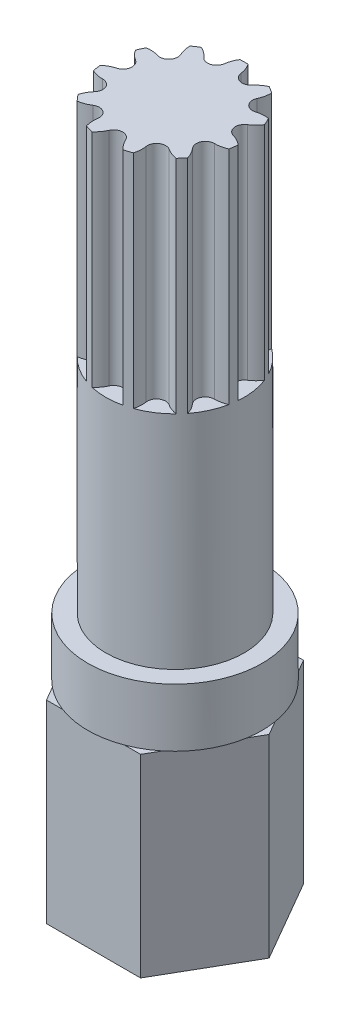
SolidWorks part; units mm, degrees
ref_plane "Front Plane" through (0, 0, 0) normal (0, 0, 1) x (1, 0, 0)
ref_plane "Top Plane" through (0, 0, 0) normal (0, 1, 0) x (1, 0, 0)
ref_plane "Right Plane" through (0, 0, 0) normal (1, 0, 0) x (0, 0, -1)
sketch "Sketch1" plane through (0, 0, 0) normal (0, 1, 0) x (1, 0, 0)
  circle A0 centre (0, 0) radius 3.15
  dimension "D1" = 6.3
extrude "Boss-Extrude1" add sketch "Sketch1" along normal blind 2.1
sketch "Sketch2" plane through (0, 2.1, 0) normal (0, 1, 0) x (1, 0, 0)
  circle A0 centre (0, 0) radius 2.5
  dimension "D1" = 5
extrude "Boss-Extrude3" add sketch "Sketch2" along normal blind 16
sketch "Gear Profile" plane through (0, 0, 0) normal (0, -1, 0) x (1, 0, 0)
  line L420 (-1.6777, -5.4575) -> (-1.7402, -5.3144)
  line L421 (-1.7402, -5.3144) -> (-1.7939, -5.1757)
  line L422 (-1.7939, -5.1757) -> (-1.8392, -5.0423)
  line L423 (-1.8392, -5.0423) -> (-1.8764, -4.916)
  line L424 (-1.8764, -4.916) -> (-1.9071, -4.7932)
  line L425 (-1.9071, -4.7932) -> (-1.9311, -4.676)
  line L426 (-1.9311, -4.676) -> (-1.9488, -4.5668)
  line L427 (-1.9488, -4.5668) -> (-1.961, -4.464)
  line L428 (-1.961, -4.464) -> (-1.9715, -4.2798)
  line L429 (-1.9715, -4.2798) -> (-1.9674, -4.1246)
  line L430 (-1.9674, -4.1246) -> (-1.9537, -4.0009)
  line L431 (-1.9537, -4.0009) -> (-1.9303, -3.8867)
  line L432 (-1.9303, -3.8867) -> (-1.8594, -3.8097)
  line L433 (-1.8594, -3.8097) -> (-1.7784, -3.7125)
  line L434 (-1.7784, -3.7125) -> (-1.7087, -3.6155)
  line L435 (-1.7087, -3.6155) -> (-1.6501, -3.5195)
  line L436 (-1.6501, -3.5195) -> (-1.6023, -3.4251)
  line L437 (-1.6023, -3.4251) -> (-1.5652, -3.3333)
  line L438 (-1.5652, -3.3333) -> (-1.5384, -3.2446)
  line L439 (-1.5384, -3.2446) -> (-1.5215, -3.1597)
  line L440 (-1.5215, -3.1597) -> (-1.5143, -3.0795)
  line L441 (-1.5143, -3.0795) -> (-1.5162, -3.0043)
  line L442 (-1.5162, -3.0043) -> (-1.5269, -2.935)
  line L443 (-1.5269, -2.935) -> (-1.5457, -2.8721)
  line L444 (-1.5457, -2.8721) -> (-1.5723, -2.8162)
  line L445 (-1.5723, -2.8162) -> (-1.606, -2.7677)
  line L446 (-1.606, -2.7677) -> (-1.6572, -2.7183)
  line L447 (-1.6572, -2.7183) -> (-1.8447, -2.5928)
  line L448 (-1.8447, -2.5928) -> (-1.984, -2.4878)
  line L449 (-1.984, -2.4878) -> (-2.1173, -2.3754)
  line L450 (-2.1173, -2.3754) -> (-2.2814, -2.2205)
  line L451 (-2.2814, -2.2205) -> (-2.341, -2.1815)
  line L452 (-2.341, -2.1815) -> (-2.3957, -2.1595)
  line L453 (-2.3957, -2.1595) -> (-2.4562, -2.146)
  line L454 (-2.4562, -2.146) -> (-2.5217, -2.1417)
  line L455 (-2.5217, -2.1417) -> (-2.5917, -2.1467)
  line L456 (-2.5917, -2.1467) -> (-2.6653, -2.1615)
  line L457 (-2.6653, -2.1615) -> (-2.742, -2.1865)
  line L458 (-2.742, -2.1865) -> (-2.8209, -2.2218)
  line L459 (-2.8209, -2.2218) -> (-2.9014, -2.2676)
  line L460 (-2.9014, -2.2676) -> (-2.9827, -2.3243)
  line L461 (-2.9827, -2.3243) -> (-3.0641, -2.3918)
  line L462 (-3.0641, -2.3918) -> (-3.1447, -2.4703)
  line L463 (-3.1447, -2.4703) -> (-3.2237, -2.5599)
  line L464 (-3.2237, -2.5599) -> (-3.3005, -2.6605)
  line L465 (-3.3005, -2.6605) -> (-3.3598, -2.7467)
  line L466 (-3.3598, -2.7467) -> (-3.4659, -2.795)
  line L467 (-3.4659, -2.795) -> (-3.5835, -2.8358)
  line L468 (-3.5835, -2.8358) -> (-3.7338, -2.8744)
  line L469 (-3.7338, -2.8744) -> (-3.9158, -2.9052)
  line L470 (-3.9158, -2.9052) -> (-4.0187, -2.9161)
  line L471 (-4.0187, -2.9161) -> (-4.1291, -2.9232)
  line L472 (-4.1291, -2.9232) -> (-4.2487, -2.9258)
  line L473 (-4.2487, -2.9258) -> (-4.3752, -2.9233)
  line L474 (-4.3752, -2.9233) -> (-4.5067, -2.9151)
  line L475 (-4.5067, -2.9151) -> (-4.6468, -2.9006)
  line L476 (-4.6468, -2.9006) -> (-4.794, -2.8791)
  line L477 (-4.794, -2.8791) -> (-4.9474, -2.85)
  line L478 (-4.9474, -2.85) -> (-5.0902, -2.8167)
  line L479 (-5.3759, -2.2235) -> (-5.3129, -2.0911)
  line L480 (-5.3129, -2.0911) -> (-5.2399, -1.953)
  line L481 (-5.2399, -1.953) -> (-5.165, -1.8245)
  line L482 (-5.165, -1.8245) -> (-5.089, -1.7059)
  line L483 (-5.089, -1.7059) -> (-5.0134, -1.5981)
  line L484 (-5.0134, -1.5981) -> (-4.9365, -1.4976)
  line L485 (-4.9365, -1.4976) -> (-4.8599, -1.4057)
  line L486 (-4.8599, -1.4057) -> (-4.7855, -1.3238)
  line L487 (-4.7855, -1.3238) -> (-4.7128, -1.2502)
  line L488 (-4.7128, -1.2502) -> (-4.5753, -1.1271)
  line L489 (-4.5753, -1.1271) -> (-4.4514, -1.0336)
  line L490 (-4.4514, -1.0336) -> (-4.3462, -0.9671)
  line L491 (-4.3462, -0.9671) -> (-4.2422, -0.9142)
  line L492 (-4.2422, -0.9142) -> (-4.1379, -0.9217)
  line L493 (-4.1379, -0.9217) -> (-4.0114, -0.9244)
  line L494 (-4.0114, -0.9244) -> (-3.8921, -0.9184)
  line L495 (-3.8921, -0.9184) -> (-3.7804, -0.9043)
  line L496 (-3.7804, -0.9043) -> (-3.6769, -0.8828)
  line L497 (-3.6769, -0.8828) -> (-3.5819, -0.8546)
  line L498 (-3.5819, -0.8546) -> (-3.4959, -0.8203)
  line L499 (-3.4959, -0.8203) -> (-3.4191, -0.7805)
  line L500 (-3.4191, -0.7805) -> (-3.3518, -0.7361)
  line L501 (-3.3518, -0.7361) -> (-3.2942, -0.6878)
  line L502 (-3.2942, -0.6878) -> (-3.2467, -0.6363)
  line L503 (-3.2467, -0.6363) -> (-3.2093, -0.5823)
  line L504 (-3.2093, -0.5823) -> (-3.1821, -0.5267)
  line L505 (-3.1821, -0.5267) -> (-3.1652, -0.4701)
  line L506 (-3.1652, -0.4701) -> (-3.1585, -0.3992)
  line L507 (-3.1585, -0.3992) -> (-3.1773, -0.1744)
  line L508 (-3.1773, -0.1744) -> (-3.1821, 0)
  line L509 (-3.1821, 0) -> (-3.1773, 0.1743)
  line L510 (-3.1773, 0.1743) -> (-3.1585, 0.3991)
  line L511 (-3.1585, 0.3991) -> (-3.1652, 0.47)
  line L512 (-3.1652, 0.47) -> (-3.1821, 0.5266)
  line L513 (-3.1821, 0.5266) -> (-3.2093, 0.5822)
  line L514 (-3.2093, 0.5822) -> (-3.2467, 0.6362)
  line L515 (-3.2467, 0.6362) -> (-3.2942, 0.6877)
  line L516 (-3.2942, 0.6877) -> (-3.3518, 0.7361)
  line L517 (-3.3518, 0.7361) -> (-3.4191, 0.7805)
  line L518 (-3.4191, 0.7805) -> (-3.4959, 0.8202)
  line L519 (-3.4959, 0.8202) -> (-3.5819, 0.8545)
  line L520 (-3.5819, 0.8545) -> (-3.6769, 0.8828)
  line L521 (-3.6769, 0.8828) -> (-3.7804, 0.9043)
  line L522 (-3.7804, 0.9043) -> (-3.8921, 0.9183)
  line L523 (-3.8921, 0.9183) -> (-4.0114, 0.9243)
  line L524 (-4.0114, 0.9243) -> (-4.1379, 0.9216)
  line L525 (-4.1379, 0.9216) -> (-4.2422, 0.9142)
  line L526 (-4.2422, 0.9142) -> (-4.3462, 0.967)
  line L527 (-4.3462, 0.967) -> (-4.4514, 1.0335)
  line L528 (-4.4514, 1.0335) -> (-4.5753, 1.127)
  line L529 (-4.5753, 1.127) -> (-4.7128, 1.2501)
  line L530 (-4.7128, 1.2501) -> (-4.7855, 1.3238)
  line L531 (-4.7855, 1.3238) -> (-4.8599, 1.4056)
  line L532 (-4.8599, 1.4056) -> (-4.9365, 1.4975)
  line L533 (-4.9365, 1.4975) -> (-5.0134, 1.598)
  line L534 (-5.0134, 1.598) -> (-5.089, 1.7059)
  line L535 (-5.089, 1.7059) -> (-5.165, 1.8244)
  line L536 (-5.165, 1.8244) -> (-5.2399, 1.9529)
  line L537 (-5.2399, 1.9529) -> (-5.3129, 2.0911)
  line L538 (-5.3129, 2.0911) -> (-5.3759, 2.2234)
  line L539 (-5.0902, 2.8167) -> (-4.9474, 2.8499)
  line L540 (-4.9474, 2.8499) -> (-4.794, 2.879)
  line L541 (-4.794, 2.879) -> (-4.6468, 2.9005)
  line L542 (-4.6468, 2.9005) -> (-4.5067, 2.9151)
  line L543 (-4.5067, 2.9151) -> (-4.3752, 2.9232)
  line L544 (-4.3752, 2.9232) -> (-4.2487, 2.9257)
  line L545 (-4.2487, 2.9257) -> (-4.1291, 2.9231)
  line L546 (-4.1291, 2.9231) -> (-4.0187, 2.916)
  line L547 (-4.0187, 2.916) -> (-3.9158, 2.9051)
  line L548 (-3.9158, 2.9051) -> (-3.7338, 2.8743)
  line L549 (-3.7338, 2.8743) -> (-3.5835, 2.8358)
  line L550 (-3.5835, 2.8358) -> (-3.4659, 2.7949)
  line L551 (-3.4659, 2.7949) -> (-3.3598, 2.7466)
  line L552 (-3.3598, 2.7466) -> (-3.3005, 2.6604)
  line L553 (-3.3005, 2.6604) -> (-3.2237, 2.5598)
  line L554 (-3.2237, 2.5598) -> (-3.1447, 2.4703)
  line L555 (-3.1447, 2.4703) -> (-3.0641, 2.3918)
  line L556 (-3.0641, 2.3918) -> (-2.9827, 2.3242)
  line L557 (-2.9827, 2.3242) -> (-2.9014, 2.2676)
  line L558 (-2.9014, 2.2676) -> (-2.8209, 2.2217)
  line L559 (-2.8209, 2.2217) -> (-2.742, 2.1864)
  line L560 (-2.742, 2.1864) -> (-2.6653, 2.1615)
  line L561 (-2.6653, 2.1615) -> (-2.5917, 2.1466)
  line L562 (-2.5917, 2.1466) -> (-2.5217, 2.1416)
  line L563 (-2.5217, 2.1416) -> (-2.4562, 2.146)
  line L564 (-2.4562, 2.146) -> (-2.3957, 2.1594)
  line L565 (-2.3957, 2.1594) -> (-2.341, 2.1815)
  line L566 (-2.341, 2.1815) -> (-2.2814, 2.2205)
  line L567 (-2.2814, 2.2205) -> (-2.1173, 2.3753)
  line L568 (-2.1173, 2.3753) -> (-1.984, 2.4878)
  line L569 (-1.984, 2.4878) -> (-1.8447, 2.5927)
  line L570 (-1.8447, 2.5927) -> (-1.6572, 2.7182)
  line L571 (-1.6572, 2.7182) -> (-1.606, 2.7676)
  line L572 (-1.606, 2.7676) -> (-1.5723, 2.8161)
  line L573 (-1.5723, 2.8161) -> (-1.5457, 2.8721)
  line L574 (-1.5457, 2.8721) -> (-1.5269, 2.935)
  line L575 (-1.5269, 2.935) -> (-1.5162, 3.0043)
  line L576 (-1.5162, 3.0043) -> (-1.5143, 3.0794)
  line L577 (-1.5143, 3.0794) -> (-1.5215, 3.1597)
  line L578 (-1.5215, 3.1597) -> (-1.5384, 3.2445)
  line L579 (-1.5384, 3.2445) -> (-1.5652, 3.3332)
  line L580 (-1.5652, 3.3332) -> (-1.6023, 3.4251)
  line L581 (-1.6023, 3.4251) -> (-1.6501, 3.5194)
  line L582 (-1.6501, 3.5194) -> (-1.7087, 3.6154)
  line L583 (-1.7087, 3.6154) -> (-1.7784, 3.7125)
  line L584 (-1.7784, 3.7125) -> (-1.8594, 3.8097)
  line L585 (-1.8594, 3.8097) -> (-1.9303, 3.8866)
  line L586 (-1.9303, 3.8866) -> (-1.9537, 4.0009)
  line L587 (-1.9537, 4.0009) -> (-1.9674, 4.1246)
  line L588 (-1.9674, 4.1246) -> (-1.9715, 4.2797)
  line L589 (-1.9715, 4.2797) -> (-1.961, 4.464)
  line L590 (-1.961, 4.464) -> (-1.9488, 4.5668)
  line L591 (-1.9488, 4.5668) -> (-1.9311, 4.6759)
  line L592 (-1.9311, 4.6759) -> (-1.9071, 4.7932)
  line L593 (-1.9071, 4.7932) -> (-1.8764, 4.9159)
  line L594 (-1.8764, 4.9159) -> (-1.8392, 5.0423)
  line L595 (-1.8392, 5.0423) -> (-1.7939, 5.1756)
  line L596 (-1.7939, 5.1756) -> (-1.7402, 5.3143)
  line L597 (-1.7402, 5.3143) -> (-1.6777, 5.4575)
  line L598 (-1.6777, 5.4575) -> (-1.6135, 5.5893)
  line L599 (-0.9715, 5.7358) -> (-0.8565, 5.6449)
  line L600 (-0.8565, 5.6449) -> (-0.7381, 5.543)
  line L601 (-0.7381, 5.543) -> (-0.6295, 5.4414)
  line L602 (-0.6295, 5.4414) -> (-0.5308, 5.3409)
  line L603 (-0.5308, 5.3409) -> (-0.4425, 5.2432)
  line L604 (-0.4425, 5.2432) -> (-0.3616, 5.1459)
  line L605 (-0.3616, 5.1459) -> (-0.2891, 5.0507)
  line L606 (-0.2891, 5.0507) -> (-0.2258, 4.96)
  line L607 (-0.2258, 4.96) -> (-0.1702, 4.8727)
  line L608 (-0.1702, 4.8727) -> (-0.0808, 4.7113)
  line L609 (-0.0808, 4.7113) -> (-0.0172, 4.5697)
  line L610 (-0.0172, 4.5697) -> (0.0242, 4.4523)
  line L611 (0.0242, 4.4523) -> (0.0526, 4.3392)
  line L612 (0.0526, 4.3392) -> (0.0222, 4.2391)
  line L613 (0.0222, 4.2391) -> (-0.0086, 4.1164)
  line L614 (-0.0086, 4.1164) -> (-0.0293, 3.9987)
  line L615 (-0.0293, 3.9987) -> (-0.0405, 3.8868)
  line L616 (-0.0405, 3.8868) -> (-0.0426, 3.7811)
  line L617 (-0.0426, 3.7811) -> (-0.0362, 3.6822)
  line L618 (-0.0362, 3.6822) -> (-0.0218, 3.5907)
  line L619 (-0.0218, 3.5907) -> (-0.0002, 3.5069)
  line L620 (-0.0002, 3.5069) -> (0.0281, 3.4314)
  line L621 (0.0281, 3.4314) -> (0.0624, 3.3646)
  line L622 (0.0624, 3.3646) -> (0.1021, 3.3068)
  line L623 (0.1021, 3.3068) -> (0.1464, 3.2583)
  line L624 (0.1464, 3.2583) -> (0.1946, 3.2194)
  line L625 (0.1946, 3.2194) -> (0.246, 3.1903)
  line L626 (0.246, 3.1903) -> (0.3136, 3.1681)
  line L627 (0.3136, 3.1681) -> (0.537, 3.1363)
  line L628 (0.537, 3.1363) -> (0.708, 3.1022)
  line L629 (0.708, 3.1022) -> (0.8769, 3.0588)
  line L630 (0.8769, 3.0588) -> (1.0919, 2.9904)
  line L631 (1.0919, 2.9904) -> (1.1625, 2.9811)
  line L632 (1.1625, 2.9811) -> (1.2214, 2.985)
  line L633 (1.2214, 2.985) -> (1.2817, 2.9991)
  line L634 (1.2817, 2.9991) -> (1.3427, 3.0236)
  line L635 (1.3427, 3.0236) -> (1.4035, 3.0585)
  line L636 (1.4035, 3.0585) -> (1.4634, 3.1038)
  line L637 (1.4634, 3.1038) -> (1.5217, 3.1596)
  line L638 (1.5217, 3.1596) -> (1.5775, 3.2256)
  line L639 (1.5775, 3.2256) -> (1.6301, 3.3019)
  line L640 (1.6301, 3.3019) -> (1.6788, 3.3882)
  line L641 (1.6788, 3.3882) -> (1.7228, 3.4843)
  line L642 (1.7228, 3.4843) -> (1.7613, 3.59)
  line L643 (1.7613, 3.59) -> (1.7937, 3.705)
  line L644 (1.7937, 3.705) -> (1.8192, 3.829)
  line L645 (1.8192, 3.829) -> (1.8352, 3.9324)
  line L646 (1.8352, 3.9324) -> (1.9099, 4.0219)
  line L647 (1.9099, 4.0219) -> (1.9981, 4.1097)
  line L648 (1.9981, 4.1097) -> (2.1168, 4.2097)
  line L649 (2.1168, 4.2097) -> (2.2674, 4.3164)
  line L650 (2.2674, 4.3164) -> (2.3554, 4.3709)
  line L651 (2.3554, 4.3709) -> (2.4518, 4.4251)
  line L652 (2.4518, 4.4251) -> (2.5584, 4.4794)
  line L653 (2.5584, 4.4794) -> (2.6735, 4.532)
  line L654 (2.6735, 4.532) -> (2.7955, 4.5817)
  line L655 (2.7955, 4.5817) -> (2.928, 4.6294)
  line L656 (2.928, 4.6294) -> (3.0699, 4.6739)
  line L657 (3.0699, 4.6739) -> (3.2208, 4.7143)
  line L658 (3.2208, 4.7143) -> (3.3639, 4.7463)
  line L659 (3.8787, 4.3357) -> (3.8793, 4.1891)
  line L660 (3.8793, 4.1891) -> (3.8735, 4.033)
  line L661 (3.8735, 4.033) -> (3.8618, 3.8847)
  line L662 (3.8618, 3.8847) -> (3.8448, 3.7449)
  line L663 (3.8448, 3.7449) -> (3.8234, 3.615)
  line L664 (3.8234, 3.615) -> (3.7978, 3.4911)
  line L665 (3.7978, 3.4911) -> (3.7686, 3.375)
  line L666 (3.7686, 3.375) -> (3.7371, 3.269)
  line L667 (3.7371, 3.269) -> (3.7036, 3.1711)
  line L668 (3.7036, 3.1711) -> (3.6331, 3.0005)
  line L669 (3.6331, 3.0005) -> (3.562, 2.8625)
  line L670 (3.562, 2.8625) -> (3.4961, 2.757)
  line L671 (3.4961, 2.757) -> (3.4253, 2.6643)
  line L672 (3.4253, 2.6643) -> (3.3281, 2.6257)
  line L673 (3.3281, 2.6257) -> (3.213, 2.5732)
  line L674 (3.213, 2.5732) -> (3.1081, 2.516)
  line L675 (3.1081, 2.516) -> (3.0136, 2.4549)
  line L676 (3.0136, 2.4549) -> (2.9296, 2.3907)
  line L677 (2.9296, 2.3907) -> (2.8563, 2.324)
  line L678 (2.8563, 2.324) -> (2.7937, 2.2557)
  line L679 (2.7937, 2.2557) -> (2.7417, 2.1866)
  line L680 (2.7417, 2.1866) -> (2.7003, 2.1174)
  line L681 (2.7003, 2.1174) -> (2.6695, 2.0489)
  line L682 (2.6695, 2.0489) -> (2.649, 1.9819)
  line L683 (2.649, 1.9819) -> (2.6387, 1.917)
  line L684 (2.6387, 1.917) -> (2.6383, 1.8551)
  line L685 (2.6383, 1.8551) -> (2.6476, 1.7967)
  line L686 (2.6476, 1.7967) -> (2.6724, 1.73)
  line L687 (2.6724, 1.73) -> (2.7869, 1.5356)
  line L688 (2.7869, 1.5356) -> (2.8668, 1.3806)
  line L689 (2.8668, 1.3806) -> (2.9382, 1.2215)
  line L690 (2.9382, 1.2215) -> (3.0188, 1.0107)
  line L691 (3.0188, 1.0107) -> (3.0555, 0.9498)
  line L692 (3.0555, 0.9498) -> (3.0953, 0.9061)
  line L693 (3.0953, 0.9061) -> (3.144, 0.8678)
  line L694 (3.144, 0.8678) -> (3.2011, 0.8354)
  line L695 (3.2011, 0.8354) -> (3.2663, 0.8096)
  line L696 (3.2663, 0.8096) -> (3.3391, 0.791)
  line L697 (3.3391, 0.791) -> (3.419, 0.7802)
  line L698 (3.419, 0.7802) -> (3.5054, 0.7777)
  line L699 (3.5054, 0.7777) -> (3.5979, 0.7842)
  line L700 (3.5979, 0.7842) -> (3.6957, 0.7999)
  line L701 (3.6957, 0.7999) -> (3.7983, 0.8255)
  line L702 (3.7983, 0.8255) -> (3.905, 0.8612)
  line L703 (3.905, 0.8612) -> (4.0151, 0.9076)
  line L704 (4.0151, 0.9076) -> (4.1279, 0.9649)
  line L705 (4.1279, 0.9649) -> (4.2187, 1.0169)
  line L706 (4.2187, 1.0169) -> (4.3353, 1.0144)
  line L707 (4.3353, 1.0144) -> (4.4589, 1.0001)
  line L708 (4.4589, 1.0001) -> (4.6111, 0.9696)
  line L709 (4.6111, 0.9696) -> (4.7884, 0.9184)
  line L710 (4.7884, 0.9184) -> (4.8859, 0.8836)
  line L711 (4.8859, 0.8836) -> (4.9884, 0.8421)
  line L712 (4.9884, 0.8421) -> (5.0973, 0.7926)
  line L713 (5.0973, 0.7926) -> (5.2102, 0.7354)
  line L714 (5.2102, 0.7354) -> (5.3251, 0.671)
  line L715 (5.3251, 0.671) -> (5.445, 0.5972)
  line L716 (5.445, 0.5972) -> (5.5683, 0.5139)
  line L717 (5.5683, 0.5139) -> (5.6939, 0.4211)
  line L718 (5.6939, 0.4211) -> (5.8081, 0.3292)
  line L719 (5.8081, -0.3293) -> (5.6939, -0.4212)
  line L720 (5.6939, -0.4212) -> (5.5683, -0.514)
  line L721 (5.5683, -0.514) -> (5.445, -0.5972)
  line L722 (5.445, -0.5972) -> (5.3251, -0.6711)
  line L723 (5.3251, -0.6711) -> (5.2102, -0.7354)
  line L724 (5.2102, -0.7354) -> (5.0973, -0.7926)
  line L725 (5.0973, -0.7926) -> (4.9884, -0.8421)
  line L726 (4.9884, -0.8421) -> (4.8859, -0.8837)
  line L727 (4.8859, -0.8837) -> (4.7884, -0.9185)
  line L728 (4.7884, -0.9185) -> (4.6111, -0.9697)
  line L729 (4.6111, -0.9697) -> (4.4589, -1.0002)
  line L730 (4.4589, -1.0002) -> (4.3353, -1.0144)
  line L731 (4.3353, -1.0144) -> (4.2187, -1.017)
  line L732 (4.2187, -1.017) -> (4.1279, -0.965)
  line L733 (4.1279, -0.965) -> (4.0151, -0.9077)
  line L734 (4.0151, -0.9077) -> (3.905, -0.8613)
  line L735 (3.905, -0.8613) -> (3.7983, -0.8255)
  line L736 (3.7983, -0.8255) -> (3.6957, -0.8)
  line L737 (3.6957, -0.8) -> (3.5979, -0.7842)
  line L738 (3.5979, -0.7842) -> (3.5054, -0.7778)
  line L739 (3.5054, -0.7778) -> (3.419, -0.7803)
  line L740 (3.419, -0.7803) -> (3.3391, -0.7911)
  line L741 (3.3391, -0.7911) -> (3.2663, -0.8097)
  line L742 (3.2663, -0.8097) -> (3.2011, -0.8354)
  line L743 (3.2011, -0.8354) -> (3.144, -0.8678)
  line L744 (3.144, -0.8678) -> (3.0953, -0.9062)
  line L745 (3.0953, -0.9062) -> (3.0555, -0.9498)
  line L746 (3.0555, -0.9498) -> (3.0188, -1.0108)
  line L747 (3.0188, -1.0108) -> (2.9382, -1.2215)
  line L748 (2.9382, -1.2215) -> (2.8668, -1.3806)
  line L749 (2.8668, -1.3806) -> (2.7869, -1.5356)
  line L750 (2.7869, -1.5356) -> (2.6724, -1.7301)
  line L751 (2.6724, -1.7301) -> (2.6476, -1.7968)
  line L752 (2.6476, -1.7968) -> (2.6383, -1.8551)
  line L753 (2.6383, -1.8551) -> (2.6387, -1.9171)
  line L754 (2.6387, -1.9171) -> (2.649, -1.9819)
  line L755 (2.649, -1.9819) -> (2.6695, -2.049)
  line L756 (2.6695, -2.049) -> (2.7003, -2.1175)
  line L757 (2.7003, -2.1175) -> (2.7417, -2.1867)
  line L758 (2.7417, -2.1867) -> (2.7937, -2.2558)
  line L759 (2.7937, -2.2558) -> (2.8563, -2.3241)
  line L760 (2.8563, -2.3241) -> (2.9296, -2.3907)
  line L761 (2.9296, -2.3907) -> (3.0136, -2.455)
  line L762 (3.0136, -2.455) -> (3.1081, -2.5161)
  line L763 (3.1081, -2.5161) -> (3.213, -2.5733)
  line L764 (3.213, -2.5733) -> (3.3281, -2.6257)
  line L765 (3.3281, -2.6257) -> (3.4253, -2.6643)
  line L766 (3.4253, -2.6643) -> (3.4961, -2.757)
  line L767 (3.4961, -2.757) -> (3.562, -2.8626)
  line L768 (3.562, -2.8626) -> (3.6331, -3.0006)
  line L769 (3.6331, -3.0006) -> (3.7036, -3.1711)
  line L770 (3.7036, -3.1711) -> (3.7371, -3.2691)
  line L771 (3.7371, -3.2691) -> (3.7686, -3.3751)
  line L772 (3.7686, -3.3751) -> (3.7978, -3.4911)
  line L773 (3.7978, -3.4911) -> (3.8234, -3.615)
  line L774 (3.8234, -3.615) -> (3.8448, -3.745)
  line L775 (3.8448, -3.745) -> (3.8618, -3.8848)
  line L776 (3.8618, -3.8848) -> (3.8735, -4.0331)
  line L777 (3.8735, -4.0331) -> (3.8793, -4.1892)
  line L778 (3.8793, -4.1892) -> (3.8787, -4.3358)
  line L779 (3.3639, -4.7463) -> (3.2208, -4.7143)
  line L780 (3.2208, -4.7143) -> (3.0699, -4.6739)
  line L781 (3.0699, -4.6739) -> (2.928, -4.6295)
  line L782 (2.928, -4.6295) -> (2.7955, -4.5818)
  line L783 (2.7955, -4.5818) -> (2.6735, -4.5321)
  line L784 (2.6735, -4.5321) -> (2.5584, -4.4795)
  line L785 (2.5584, -4.4795) -> (2.4518, -4.4252)
  line L786 (2.4518, -4.4252) -> (2.3554, -4.3709)
  line L787 (2.3554, -4.3709) -> (2.2674, -4.3164)
  line L788 (2.2674, -4.3164) -> (2.1168, -4.2097)
  line L789 (2.1168, -4.2097) -> (1.9981, -4.1098)
  line L790 (1.9981, -4.1098) -> (1.9099, -4.022)
  line L791 (1.9099, -4.022) -> (1.8352, -3.9324)
  line L792 (1.8352, -3.9324) -> (1.8192, -3.829)
  line L793 (1.8192, -3.829) -> (1.7937, -3.7051)
  line L794 (1.7937, -3.7051) -> (1.7613, -3.5901)
  line L795 (1.7613, -3.5901) -> (1.7228, -3.4844)
  line L796 (1.7228, -3.4844) -> (1.6788, -3.3883)
  line L797 (1.6788, -3.3883) -> (1.6301, -3.3019)
  line L798 (1.6301, -3.3019) -> (1.5775, -3.2257)
  line L799 (1.5775, -3.2257) -> (1.5217, -3.1596)
  line L800 (1.5217, -3.1596) -> (1.4634, -3.1039)
  line L801 (1.4634, -3.1039) -> (1.4035, -3.0586)
  line L802 (1.4035, -3.0586) -> (1.3427, -3.0237)
  line L803 (1.3427, -3.0237) -> (1.2817, -2.9992)
  line L804 (1.2817, -2.9992) -> (1.2214, -2.9851)
  line L805 (1.2214, -2.9851) -> (1.1625, -2.9812)
  line L806 (1.1625, -2.9812) -> (1.0919, -2.9905)
  line L807 (1.0919, -2.9905) -> (0.8769, -3.0588)
  line L808 (0.8769, -3.0588) -> (0.708, -3.1023)
  line L809 (0.708, -3.1023) -> (0.537, -3.1364)
  line L810 (0.537, -3.1364) -> (0.3136, -3.1681)
  line L811 (0.3136, -3.1681) -> (0.246, -3.1904)
  line L812 (0.246, -3.1904) -> (0.1946, -3.2194)
  line L813 (0.1946, -3.2194) -> (0.1464, -3.2583)
  line L814 (0.1464, -3.2583) -> (0.1021, -3.3068)
  line L815 (0.1021, -3.3068) -> (0.0624, -3.3647)
  line L816 (0.0624, -3.3647) -> (0.0281, -3.4315)
  line L817 (0.0281, -3.4315) -> (-0.0002, -3.507)
  line L818 (-0.0002, -3.507) -> (-0.0218, -3.5907)
  line L819 (-0.0218, -3.5907) -> (-0.0362, -3.6823)
  line L820 (-0.0362, -3.6823) -> (-0.0426, -3.7811)
  line L821 (-0.0426, -3.7811) -> (-0.0405, -3.8868)
  line L822 (-0.0405, -3.8868) -> (-0.0293, -3.9988)
  line L823 (-0.0293, -3.9988) -> (-0.0086, -4.1165)
  line L824 (-0.0086, -4.1165) -> (0.0222, -4.2392)
  line L825 (0.0222, -4.2392) -> (0.0526, -4.3393)
  line L826 (0.0526, -4.3393) -> (0.0242, -4.4524)
  line L827 (0.0242, -4.4524) -> (-0.0172, -4.5698)
  line L828 (-0.0172, -4.5698) -> (-0.0808, -4.7113)
  line L829 (-0.0808, -4.7113) -> (-0.1702, -4.8728)
  line L830 (-0.1702, -4.8728) -> (-0.2258, -4.9601)
  line L831 (-0.2258, -4.9601) -> (-0.2891, -5.0508)
  line L832 (-0.2891, -5.0508) -> (-0.3616, -5.146)
  line L833 (-0.3616, -5.146) -> (-0.4425, -5.2433)
  line L834 (-0.4425, -5.2433) -> (-0.5308, -5.341)
  line L835 (-0.5308, -5.341) -> (-0.6295, -5.4414)
  line L836 (-0.6295, -5.4414) -> (-0.7381, -5.5431)
  line L837 (-0.7381, -5.5431) -> (-0.8565, -5.645)
  line L838 (-0.8565, -5.645) -> (-0.9715, -5.7359)
  line L839 (-1.6135, -5.5894) -> (-1.6777, -5.4575)
  arc A7 (-5.3759, -2.2235) -> (-5.0902, -2.8167) centre (0, 0) ccw
  arc A8 (-5.0902, 2.8167) -> (-5.3759, 2.2234) centre (0, -0.0001) ccw
  arc A9 (-0.9715, 5.7358) -> (-1.6135, 5.5893) centre (0, -0.0001) ccw
  arc A10 (3.8787, 4.3357) -> (3.3639, 4.7463) centre (-0.0001, -0.0001) ccw
  arc A11 (5.8081, -0.3293) -> (5.8081, 0.3292) centre (-0.0001, 0) ccw
  arc A12 (3.3639, -4.7463) -> (3.8787, -4.3358) centre (-0.0001, 0) ccw
  arc A13 (-1.6135, -5.5894) -> (-0.9715, -5.7359) centre (0, 0) ccw
ref_plane "Plane2" through (0, 5.9, 0) normal (0, 1, 0) x (1, 0, 0)
ref_plane "Plane4" through (0, 8.1, 0) normal (0, 1, 0) x (1, 0, 0)
sketch "Sketch8" plane through (0, 18.1, 0) normal (0, 1, 0) x (1, 0, 0)
  arc A0 (-0.8749, -1.9145) -> (-0.8716, -1.8825) centre (-1.1988, -1.8653) ccw
  arc A1 (-0.2845, -2.0549) -> (-0.2991, -2.0836) centre (0, -2.2173) ccw
  arc A2 (0.2845, -2.0549) -> (-0.2845, -2.0549) centre (0, -2.2173) ccw
  arc A3 (0.2991, -2.0836) -> (0.2845, -2.0549) centre (0, -2.2173) ccw
  arc A4 (0.8716, -1.8825) -> (0.8749, -1.9145) centre (1.1988, -1.8653) ccw
  arc A5 (1.3781, -1.5911) -> (1.3503, -1.5748) centre (1.1988, -1.8653) ccw
  arc A6 (2.0195, -0.5935) -> (1.9873, -0.5948) centre (2.0169, -0.9211) ccw
  arc A7 (1.751, -1.1124) -> (1.7711, -1.1376) centre (2.0169, -0.9211) ccw
  arc A8 (2.0744, 0.0108) -> (2.1049, 0.0005) centre (2.1947, 0.3156) ccw
  arc A9 (2.0198, 0.5926) -> (1.9934, 0.574) centre (2.1947, 0.3156) ccw
  arc A10 (2.0195, -0.5935) -> (2.4493, -0.5015) centre (2.0276, 0.4185) ccw
  arc A11 (1.9873, -0.5948) -> (1.751, -1.1124) centre (2.0169, -0.9211) ccw
  arc A12 (1.9829, -1.5226) -> (1.7711, -1.1376) centre (1.0115, -1.8064) ccw
  arc A13 (1.7893, -1.7461) -> (1.9829, -1.5226) centre (0, 0) ccw
  arc A14 (1.3781, -1.5911) -> (1.7893, -1.7461) centre (1.9319, -0.7441) ccw
  arc A15 (1.3503, -1.5748) -> (0.8716, -1.8825) centre (1.1988, -1.8653) ccw
  arc A16 (0.8449, -2.353) -> (0.8749, -1.9145) centre (-0.1257, -2.0665) ccw
  arc A17 (0.5613, -2.4363) -> (0.8449, -2.353) centre (0, 0) ccw
  arc A18 (0.2991, -2.0836) -> (0.5613, -2.4363) centre (1.2229, -1.6705) ccw
  arc A19 (-0.5613, -2.4363) -> (-0.2991, -2.0836) centre (-1.2229, -1.6705) ccw
  arc A20 (-0.8449, -2.353) -> (-0.5613, -2.4363) centre (0, 0) ccw
  arc A21 (-0.8749, -1.9145) -> (-0.8449, -2.353) centre (0.1257, -2.0665) ccw
  arc A22 (2.4493, -0.5015) -> (2.4913, -0.2089) centre (0, 0) ccw
  arc A23 (2.4913, -0.2089) -> (2.1049, 0.0005) centre (1.8275, -0.9727) ccw
  arc A24 (1.9934, 0.574) -> (2.0744, 0.0108) centre (2.1947, 0.3156) ccw
  arc A25 (2.0198, 0.5926) -> (2.3316, 0.9023) centre (1.4794, 1.4482) ccw
  arc A26 (2.3316, 0.9023) -> (2.2088, 1.1712) centre (0, 0) ccw
  arc A27 (-1.3503, -1.5748) -> (-1.3781, -1.5911) centre (-1.1988, -1.8653) ccw
  arc A28 (-1.7711, -1.1376) -> (-1.751, -1.1124) centre (-2.0169, -0.9211) ccw
  arc A29 (-1.9873, -0.5948) -> (-2.0195, -0.5935) centre (-2.0169, -0.9211) ccw
  arc A30 (-2.1049, 0.0005) -> (-2.0744, 0.0108) centre (-2.1947, 0.3156) ccw
  arc A31 (-1.9934, 0.574) -> (-2.0198, 0.5926) centre (-2.1947, 0.3156) ccw
  arc A32 (-0.8716, -1.8825) -> (-1.3503, -1.5748) centre (-1.1988, -1.8653) ccw
  arc A33 (-1.7893, -1.7461) -> (-1.3781, -1.5911) centre (-1.9319, -0.7441) ccw
  arc A34 (-1.9829, -1.5226) -> (-1.7893, -1.7461) centre (0, 0) ccw
  arc A35 (-1.7711, -1.1376) -> (-1.9829, -1.5226) centre (-1.0115, -1.8064) ccw
  arc A36 (-1.751, -1.1124) -> (-1.9873, -0.5948) centre (-2.0169, -0.9211) ccw
  arc A37 (-2.4493, -0.5015) -> (-2.0195, -0.5935) centre (-2.0276, 0.4185) ccw
  arc A38 (-2.4913, -0.2089) -> (-2.4493, -0.5015) centre (0, 0) ccw
  arc A39 (-2.1049, 0.0005) -> (-2.4913, -0.2089) centre (-1.8275, -0.9727) ccw
  arc A40 (-2.0744, 0.0108) -> (-1.9934, 0.574) centre (-2.1947, 0.3156) ccw
  arc A41 (-2.3316, 0.9023) -> (-2.0198, 0.5926) centre (-1.4794, 1.4482) ccw
  arc A42 (-1.7705, 1.1384) -> (-1.7393, 1.1306) centre (-1.6757, 1.452) ccw
  arc A43 (-1.3667, 1.5606) -> (-1.3788, 1.5905) centre (-1.6757, 1.452) ccw
  arc A44 (-0.874, 1.9149) -> (-0.8519, 1.8915) centre (-0.6247, 2.1275) ccw
  arc A45 (-0.306, 2.0518) -> (-0.3001, 2.0834) centre (-0.6247, 2.1275) ccw
  arc A46 (1.7393, 1.1306) -> (1.7705, 1.1384) centre (1.6757, 1.452) ccw
  arc A47 (1.3788, 1.5905) -> (1.3667, 1.5606) centre (1.6757, 1.452) ccw
  arc A48 (2.2088, 1.1712) -> (1.7705, 1.1384) centre (2.0633, 0.1697) ccw
  arc A49 (1.3667, 1.5606) -> (1.7393, 1.1306) centre (1.6757, 1.452) ccw
  arc A50 (1.3788, 1.5905) -> (1.4736, 2.0196) centre (0.4616, 2.0182) ccw
  arc A51 (1.4736, 2.0196) -> (1.2249, 2.1794) centre (0, 0) ccw
  arc A52 (0.8519, 1.8915) -> (0.874, 1.9149) centre (0.6247, 2.1275) ccw
  arc A53 (0.3001, 2.0834) -> (0.306, 2.0518) centre (0.6247, 2.1275) ccw
  arc A54 (1.2249, 2.1794) -> (0.874, 1.9149) centre (1.644, 1.2583) ccw
  arc A55 (0.306, 2.0518) -> (0.8519, 1.8915) centre (0.6247, 2.1275) ccw
  arc A56 (0.3001, 2.0834) -> (0.1478, 2.4957) centre (-0.7028, 1.9474) ccw
  arc A57 (0.1478, 2.4957) -> (0, 2.5001) centre (0, 0) ccw
  arc A58 (0, 2.5001) -> (-0.1478, 2.4957) centre (0, 0) ccw
  arc A59 (-0.1478, 2.4957) -> (-0.3001, 2.0834) centre (0.7028, 1.9474) ccw
  arc A60 (-0.8519, 1.8915) -> (-0.306, 2.0518) centre (-0.6247, 2.1275) ccw
  arc A61 (-0.874, 1.9149) -> (-1.2249, 2.1794) centre (-1.644, 1.2583) ccw
  arc A62 (-1.2249, 2.1794) -> (-1.4736, 2.0196) centre (0, 0) ccw
  arc A63 (-1.4736, 2.0196) -> (-1.3788, 1.5905) centre (-0.4616, 2.0182) ccw
  arc A64 (-1.7393, 1.1306) -> (-1.3667, 1.5606) centre (-1.6757, 1.452) ccw
  arc A65 (-1.7705, 1.1384) -> (-2.2088, 1.1712) centre (-2.0633, 0.1697) ccw
  arc A66 (-2.2088, 1.1712) -> (-2.3316, 0.9023) centre (0, 0) ccw
  circle A68 centre (0, 0) radius 0.7859 construction
  circle A69 centre (0, 0) radius 1.8897 construction
extrude "Cut-Extrude5" cut sketch "Sketch8" against normal blind 8 flip side to cut
sketch "Sketch9" plane through (0, 0, 0) normal (0, -1, 0) x (1, 0, 0)
  line L0 (3.4, 0) -> (1.7, 2.9445)
  line L1 (1.7, 2.9445) -> (-1.7, 2.9445)
  line L2 (-1.7, 2.9445) -> (-3.4, 0)
  line L3 (-3.4, 0) -> (-1.7, -2.9445)
  line L4 (-1.7, -2.9445) -> (1.7, -2.9445)
  line L5 (1.7, -2.9445) -> (3.4, 0)
  circle A0 centre (0, 0) radius 3.4 construction
extrude "Boss-Extrude4" add sketch "Sketch9" along normal blind 7
